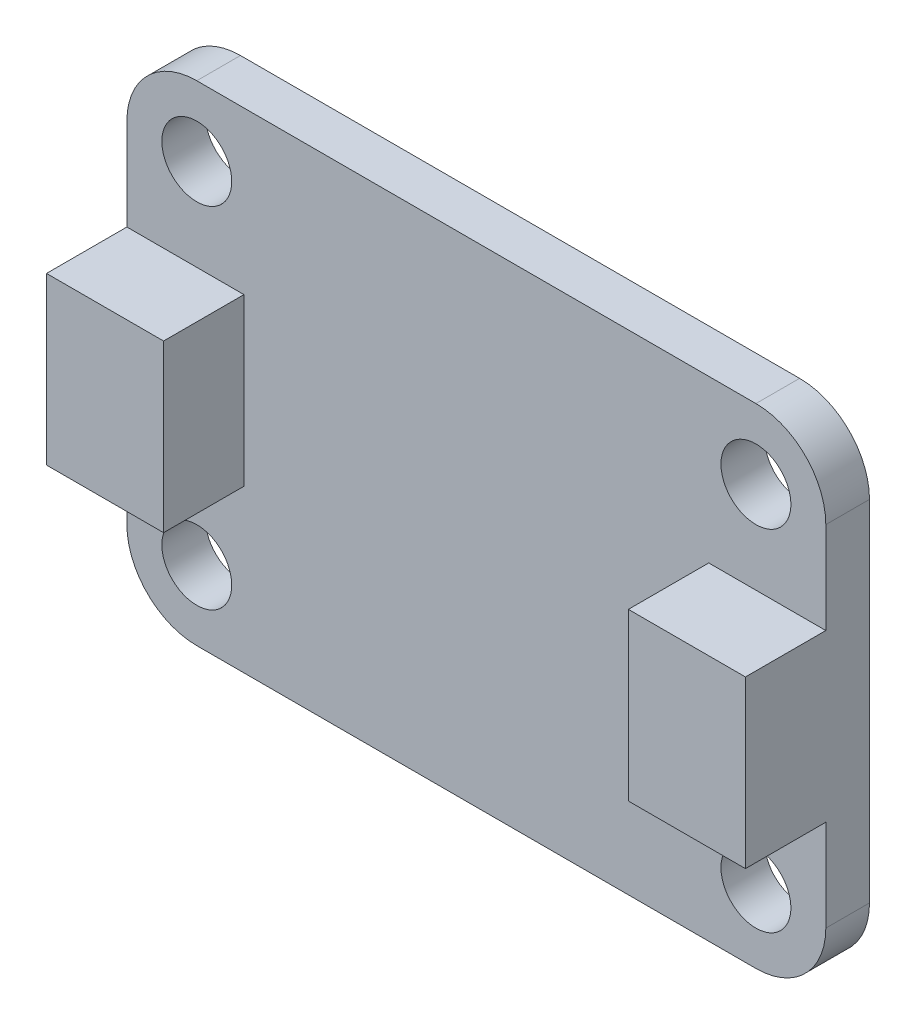
SolidWorks part; units mm, degrees
ref_plane "Front Plane" through (0, 0, 0) normal (0, 0, 1) x (1, 0, 0)
ref_plane "Top Plane" through (0, 0, 0) normal (0, 1, 0) x (1, 0, 0)
ref_plane "Right Plane" through (0, 0, 0) normal (1, 0, 0) x (0, 0, -1)
sketch "Sketch1" plane through (0, 0, 0) normal (0, 0, 1) x (1, 0, 0)
  line L1 (-12.7, 8.89) -> (12.7, 8.89)
  line L2 (-12.7, 8.89) -> (-12.7, -8.89)
  line L3 (-12.7, -8.89) -> (12.7, -8.89)
  line L4 (12.7, 8.89) -> (12.7, -8.89)
  line L5 (-12.7, 8.89) -> (12.7, -8.89) construction
  line L6 (-12.7, -8.89) -> (12.7, 8.89) construction
  point P0 (0, 0)
  dimension "D1" = 25.4
  dimension "D2" = 17.78
extrude "Boss-Extrude1" add sketch "Sketch1" along normal mid plane 1.5875
sketch "Sketch2" plane through (0, 0, 0.7937) normal (0, 0, 1) x (1, 0, 0)
  line L0 (12.7, -8.89) -> (12.7, 8.89) construction
  line L1 (12.7, -3.0162) -> (8.4455, -3.0162)
  line L2 (12.7, -3.0162) -> (12.7, 3.0162)
  line L3 (12.7, 3.0162) -> (8.4455, 3.0162)
  line L4 (8.4455, -3.0162) -> (8.4455, 3.0162)
  line L5 (12.7, -3.0162) -> (8.4455, 3.0162) construction
  line L6 (12.7, 3.0162) -> (8.4455, -3.0162) construction
  line L7 (0, -0.8731) -> (0, 0.8731) construction
  line L8 (-12.7, 3.0162) -> (-8.4455, 3.0162)
  line L9 (-8.4455, -3.0162) -> (-8.4455, 3.0162)
  line L10 (-12.7, -3.0162) -> (-8.4455, -3.0162)
  line L11 (-12.7, -3.0162) -> (-12.7, 3.0162)
  point P4 (10.5728, 0)
  dimension "D1" = 6.0325
  dimension "D2" = 4.2545
  dimension "D3" = 0
extrude "Boss-Extrude2" add sketch "Sketch2" along normal blind 2.921
sketch "Sketch3" plane through (0, 0, 0.7937) normal (0, 0, 1) x (1, 0, 0)
  line L0 (12.7, 8.89) -> (-12.7, 8.89) construction
  line L1 (-12.7, 8.89) -> (-12.7, 3.0162) construction
  line L2 (-12.7, -3.0162) -> (-12.7, -8.89) construction
  line L3 (-12.7, -8.89) -> (12.7, -8.89) construction
  line L4 (0, -2.4797) -> (0, 2.4797) construction
  circle A0 centre (-10.16, 6.35) radius 1.27
  circle A3 centre (-10.16, -6.35) radius 1.27
  circle A4 centre (10.16, -6.35) radius 1.27
  circle A5 centre (10.16, 6.35) radius 1.27
  dimension "D1" = 2.54
  dimension "D2" = 2.54
  dimension "D3" = 2.54
  dimension "D4" = 2.54
  dimension "D5" = 2.54
extrude "Cut-Extrude1" cut sketch "Sketch3" against normal through all
fillet "Fillet1" radius 2.54 4 edges at (12.7, 8.89, 0) (12.7, -8.89, 0) (-12.7, -8.89, 0) (-12.7, 8.89, 0)
